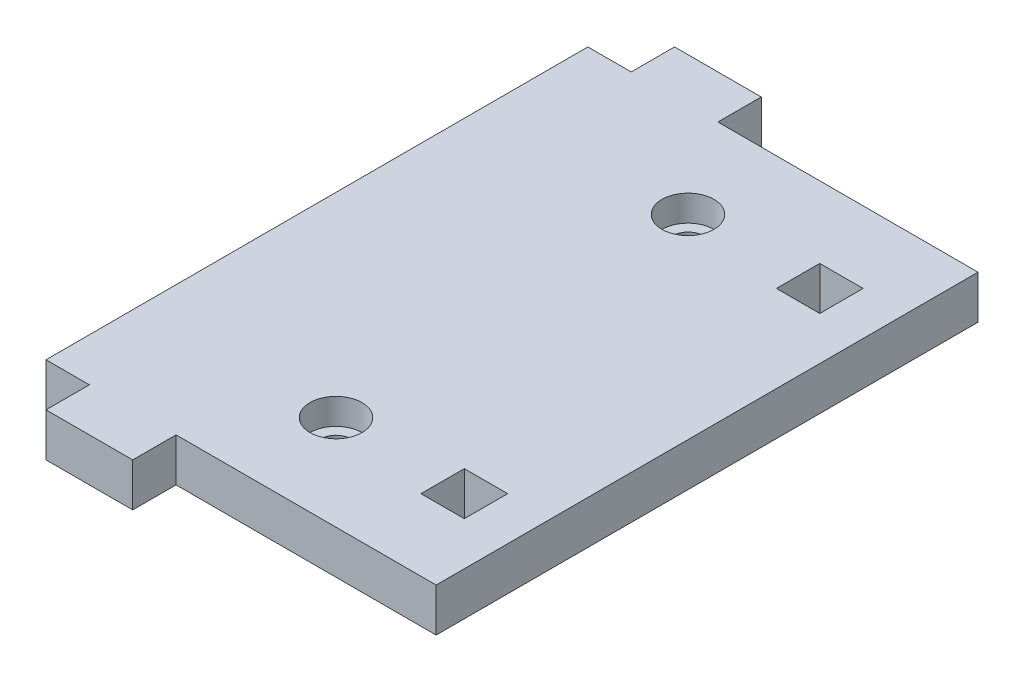
SolidWorks part; units mm, degrees
ref_plane "Front Plane" through (0, 0, 0) normal (0, 0, 1) x (1, 0, 0)
ref_plane "Top Plane" through (0, 0, 0) normal (0, 1, 0) x (1, 0, 0)
ref_plane "Right Plane" through (0, 0, 0) normal (1, 0, 0) x (0, 0, -1)
sketch "Sketch1" plane through (0, 0, 0) normal (0, 1, 0) x (1, 0, 0)
  line L0 (-116.895, -11.7675) -> (73.0758, -11.7675) construction
  line L1 (-21.9096, 19.4825) -> (23.0904, 19.4825)
  line L2 (-21.9096, 19.4825) -> (-21.9096, -43.0175)
  line L3 (-21.9096, -43.0175) -> (23.0904, -43.0175)
  line L4 (23.0904, 19.4825) -> (23.0904, -43.0175)
  line L5 (-16.9096, 19.4825) -> (-6.9096, 19.4825)
  line L6 (-16.9096, 19.4825) -> (-16.9096, 24.4825)
  line L7 (-16.9096, 24.4825) -> (-6.9096, 24.4825)
  line L8 (-6.9096, 19.4825) -> (-6.9096, 24.4825)
  line L9 (13.0904, -29.7675) -> (18.0904, -29.7675)
  line L10 (13.0904, 11.2325) -> (18.0904, 11.2325)
  line L11 (13.0904, 11.2325) -> (13.0904, 6.2325)
  line L12 (13.0904, 6.2325) -> (18.0904, 6.2325)
  line L13 (18.0904, 11.2325) -> (18.0904, 6.2325)
  line L14 (18.0904, -34.7675) -> (18.0904, -29.7675)
  line L15 (13.0904, -34.7675) -> (18.0904, -34.7675)
  line L16 (13.0904, -34.7675) -> (13.0904, -29.7675)
  line L17 (-16.9096, -48.0175) -> (-6.9096, -48.0175)
  line L18 (-6.9096, -43.0175) -> (-6.9096, -48.0175)
  line L19 (-16.9096, -43.0175) -> (-6.9096, -43.0175)
  line L20 (-16.9096, -43.0175) -> (-16.9096, -48.0175)
  circle A0 centre (0.5904, 8.5325) radius 1.75
  circle A1 centre (0.5904, -32.0675) radius 1.75
  point P11 (-21.9096, -11.7675)
  dimension "D10" = 22.5
  dimension "D1" = 45
  dimension "D2" = 62.5
  dimension "D3" = 10
  dimension "D4" = 5
  dimension "D5" = 5
  dimension "D6" = 18
  dimension "D7" = 5
  dimension "D8" = 5
  dimension "D9" = 5
  dimension "D11" = 20.3
extrude "Boss-Extrude1" add sketch "Sketch1" along normal blind 5 contours L2 L0 L4 L1 A0 L10 L13 L12 L11 | L0 L2 L3 L4 L15 L16 L9 L14 A1 | L3 L20 L17 L18 | L1 L8 L7 L6
sketch "Sketch2" plane through (0, 5, 0) normal (0, 1, 0) x (1, 0, 0)
  circle A0 centre (0.5904, -32.0675) radius 3
  circle A1 centre (0.5904, 8.5325) radius 3
extrude "Cut-Extrude1" cut sketch "Sketch2" against normal blind 3
